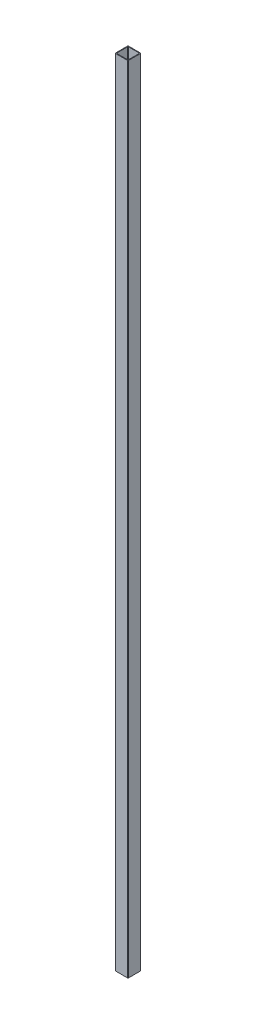
SolidWorks part; units mm, degrees
ref_plane "Спереди" through (0, 0, 0) normal (0, 0, 1) x (1, 0, 0)
ref_plane "Сверху" through (0, 0, 0) normal (0, 1, 0) x (1, 0, 0)
ref_plane "Справа" through (0, 0, 0) normal (1, 0, 0) x (0, 0, -1)
sketch "Эскиз2" plane through (0, 0, 0) normal (0, 1, 0) x (1, 0, 0)
  line L1 (-18, 20) -> (18, 20)
  line L2 (-20, 18) -> (-20, -18)
  line L3 (-18, -20) -> (18, -20)
  line L4 (20, 18) -> (20, -18)
  line L5 (-20, 20) -> (20, -20) construction
  line L6 (-20, -20) -> (20, 20) construction
  line L7 (16, -18) -> (-16, -18)
  line L8 (18, -16) -> (18, 16)
  line L9 (16, 18) -> (-16, 18)
  line L10 (-18, -16) -> (-18, 16)
  line L11 (18, -18) -> (-18, 18) construction
  line L12 (18, 18) -> (-18, -18) construction
  arc A0 (16, -18) -> (18, -16) centre (16, -16) ccw
  arc A1 (18, -20) -> (20, -18) centre (18, -18) ccw
  arc A2 (-20, -18) -> (-18, -20) centre (-18, -18) ccw
  arc A3 (-16, -18) -> (-18, -16) centre (-16, -16) cw
  arc A4 (18, 20) -> (20, 18) centre (18, 18) cw
  arc A5 (18, 16) -> (16, 18) centre (16, 16) ccw
  arc A6 (-18, 20) -> (-20, 18) centre (-18, 18) ccw
  arc A7 (-16, 18) -> (-18, 16) centre (-16, 16) ccw
  point P0 (0, 0)
  point P6 (0, 0)
  dimension "D5" = 2
  dimension "D1" = 40
  dimension "D2" = 40
  dimension "D3" = 2
  dimension "D4" = 2
extrude "Бобышка-Вытянуть1" add sketch "Эскиз2" along normal blind 2460
